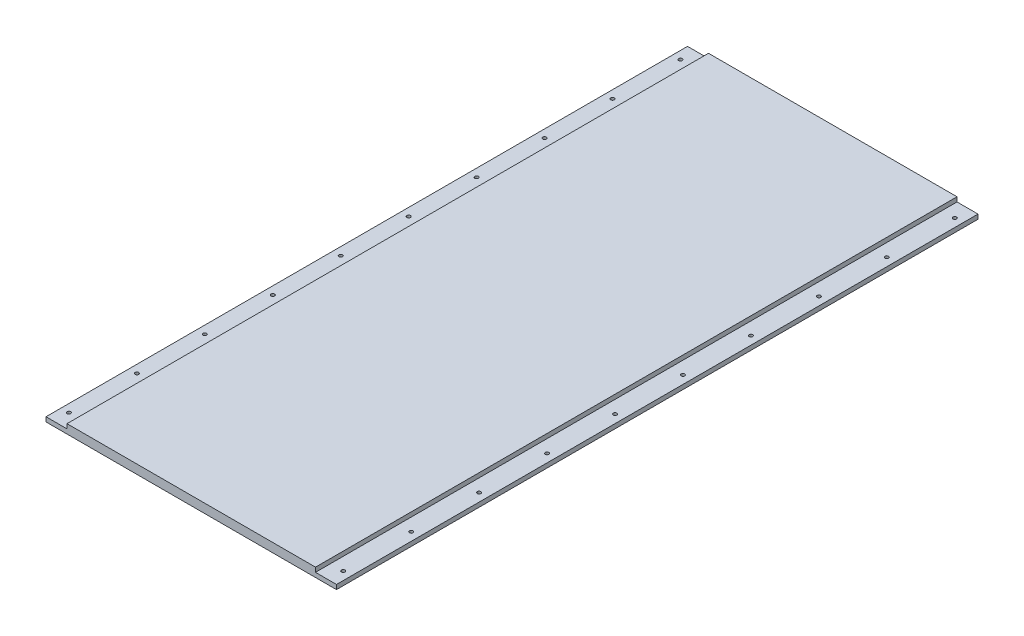
SolidWorks part; units mm, degrees
ref_plane "Front Plane" through (0, 0, 0) normal (0, 0, 1) x (1, 0, 0)
ref_plane "Top Plane" through (0, 0, 0) normal (0, 1, 0) x (1, 0, 0)
ref_plane "Right Plane" through (0, 0, 0) normal (1, 0, 0) x (0, 0, -1)
sketch "Sketch1" plane through (0, 0, 0) normal (0, 1, 0) x (1, 0, 0)
  line L1 (-48.45, -107) -> (48.45, -107)
  line L2 (-48.45, -107) -> (-48.45, 107)
  line L3 (-48.45, 107) -> (48.45, 107)
  line L4 (48.45, -107) -> (48.45, 107)
  line L5 (-48.45, -107) -> (48.45, 107) construction
  line L6 (-48.45, 107) -> (48.45, -107) construction
  point P0 (0, 0)
  dimension "D1" = 96.9
  dimension "D2" = 214
extrude "Boss-Extrude1" add sketch "Sketch1" along normal blind 3
sketch "Sketch2" plane through (0, 3, 0) normal (0, 1, 0) x (1, 0, 0)
  line L0 (-48.45, -107) -> (48.45, -107) construction
  line L1 (48.45, 107) -> (41.45, 107)
  line L2 (48.45, 107) -> (48.45, -107)
  line L3 (48.45, -107) -> (41.45, -107)
  line L4 (41.45, 107) -> (41.45, -107)
  line L6 (-48.45, 107) -> (-41.45, 107)
  line L7 (-48.45, 107) -> (-48.45, -107)
  line L8 (-48.45, -107) -> (-41.45, -107)
  line L9 (-41.45, 107) -> (-41.45, -107)
  dimension "D1" = 7
extrude "Cut-Extrude1" cut sketch "Sketch2" against normal blind 1.5
hole_wizard "#0-80 Tapped Hole1" positions "Sketch4" profile "Sketch3" tap size "#0-80" standard "ANSI Inch"
sketch "Sketch4" plane through (0, 3, 0) normal (0, 1, 0) x (1, 0, 0)
  circle A0 centre (45.7, 102) radius 1.7321 construction
  point P0 (45.7, -102)
  point P3 (-45.8, -102)
  point P13 (45.7, -79.3333)
  point P14 (-45.8, -79.3333)
  point P15 (45.7, -56.6667)
  point P16 (-45.8, -56.6667)
  point P17 (45.7, -34)
  point P18 (-45.8, -34)
  point P19 (45.7, -11.3333)
  point P20 (-45.8, -11.3333)
  point P21 (45.7, 11.3333)
  point P22 (-45.8, 11.3333)
  point P23 (45.7, 34)
  point P24 (-45.8, 34)
  point P25 (45.7, 56.6667)
  point P26 (-45.8, 56.6667)
  point P27 (45.7, 79.3333)
  point P28 (-45.8, 79.3333)
  point P29 (45.7, 102)
  point P30 (-45.8, 102)
  dimension "D1" = 10
sketch "Sketch3" plane through (45.7, 3, 102) normal (1, 0, 0) x (0, 0, 1)
  line L0 (0, 0) -> (0, 4.3584)
  line L1 (0, 4.3584) -> (0.5956, 4.0005)
  line L2 (0.5956, 4.0005) -> (0.5956, 0)
  line L5 (0.5956, 0) -> (0, 0)
  line L10 (0, 4.3584) -> (-0.5956, 4.0005) construction
  line L11 (0, -6.35) -> (0, 107.95) construction
  dimension "Tap Drill Dia." = 1.1913
  dimension "Tap Drill Depth" = 4.0005
  dimension "Drill Angle" = 118
cosmetic thread "Hole Thread1" parameters "D1"=3, "D2"=1.524
cosmetic thread "Hole Thread2" parameters "D1"=3, "D2"=1.524
cosmetic thread "Hole Thread3" parameters "D1"=3, "D2"=1.524
cosmetic thread "Hole Thread4" parameters "D1"=3, "D2"=1.524
cosmetic thread "Hole Thread5" parameters "D1"=3, "D2"=1.524
cosmetic thread "Hole Thread6" parameters "D1"=3, "D2"=1.524
cosmetic thread "Hole Thread7" parameters "D1"=3, "D2"=1.524
cosmetic thread "Hole Thread8" parameters "D1"=3, "D2"=1.524
cosmetic thread "Hole Thread9" parameters "D1"=3, "D2"=1.524
cosmetic thread "Hole Thread10" parameters "D1"=3, "D2"=1.524
cosmetic thread "Hole Thread11" parameters "D1"=3, "D2"=1.524
cosmetic thread "Hole Thread12" parameters "D1"=3, "D2"=1.524
cosmetic thread "Hole Thread13" parameters "D1"=3, "D2"=1.524
cosmetic thread "Hole Thread14" parameters "D1"=3, "D2"=1.524
cosmetic thread "Hole Thread15" parameters "D1"=3, "D2"=1.524
cosmetic thread "Hole Thread16" parameters "D1"=3, "D2"=1.524
cosmetic thread "Hole Thread17" parameters "D1"=3, "D2"=1.524
cosmetic thread "Hole Thread18" parameters "D1"=3, "D2"=1.524
cosmetic thread "Hole Thread19" parameters "D1"=3, "D2"=1.524
cosmetic thread "Hole Thread20" parameters "D1"=3, "D2"=1.524
